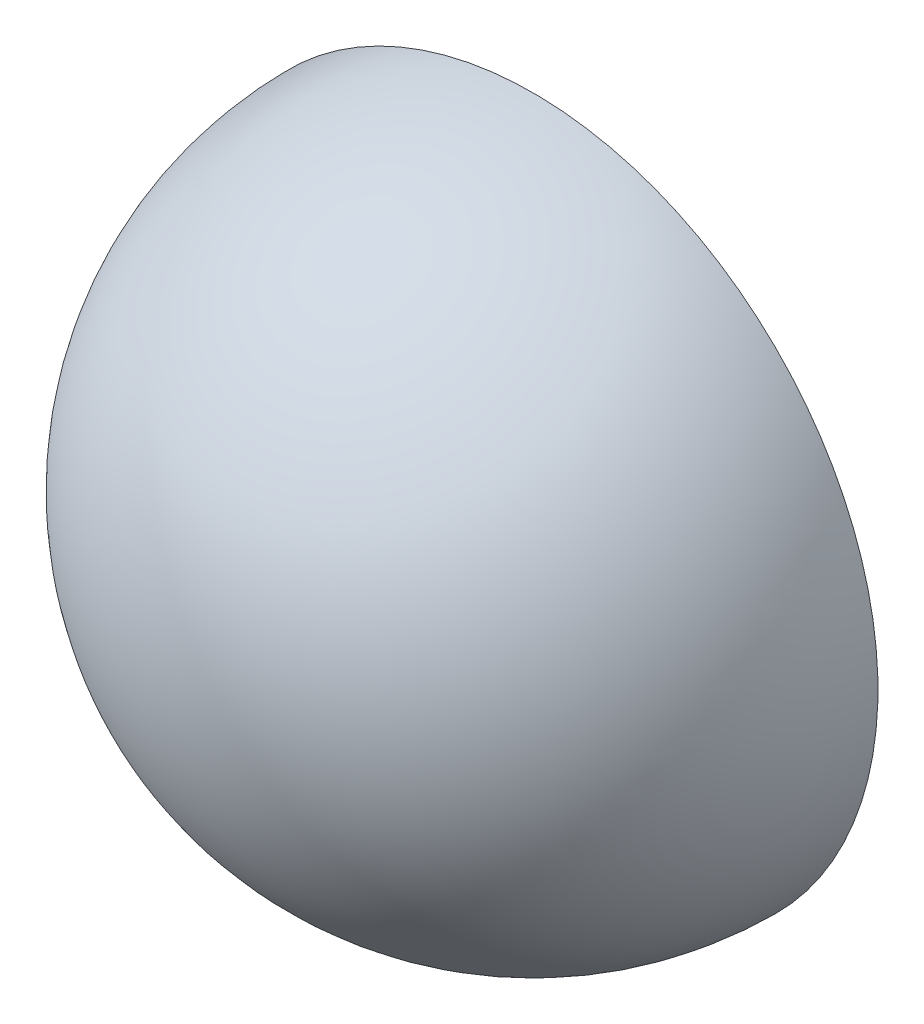
SolidWorks part; units mm, degrees
material "玻璃"
ref_plane "前视基准面" through (0, 0, 0) normal (0, 0, 1) x (1, 0, 0)
ref_plane "上视基准面" through (0, 0, 0) normal (0, 1, 0) x (1, 0, 0)
ref_plane "右视基准面" through (0, 0, 0) normal (1, 0, 0) x (0, 0, -1)
sketch "草图1" plane through (0, 0, 0) normal (0, 0, 1) x (1, 0, 0)
  line L0 (0, 100) -> (0, 98)
  line L1 (0, -98) -> (0, -100)
  arc A0 (0, -100) -> (0, 100) centre (0, 0) ccw
  arc A1 (0, -98) -> (0, 98) centre (0, 0) ccw
  dimension "D1" = 200
  dimension "D2" = 2
revolve "旋转3" add sketch "草图1" angle 180 about L0
